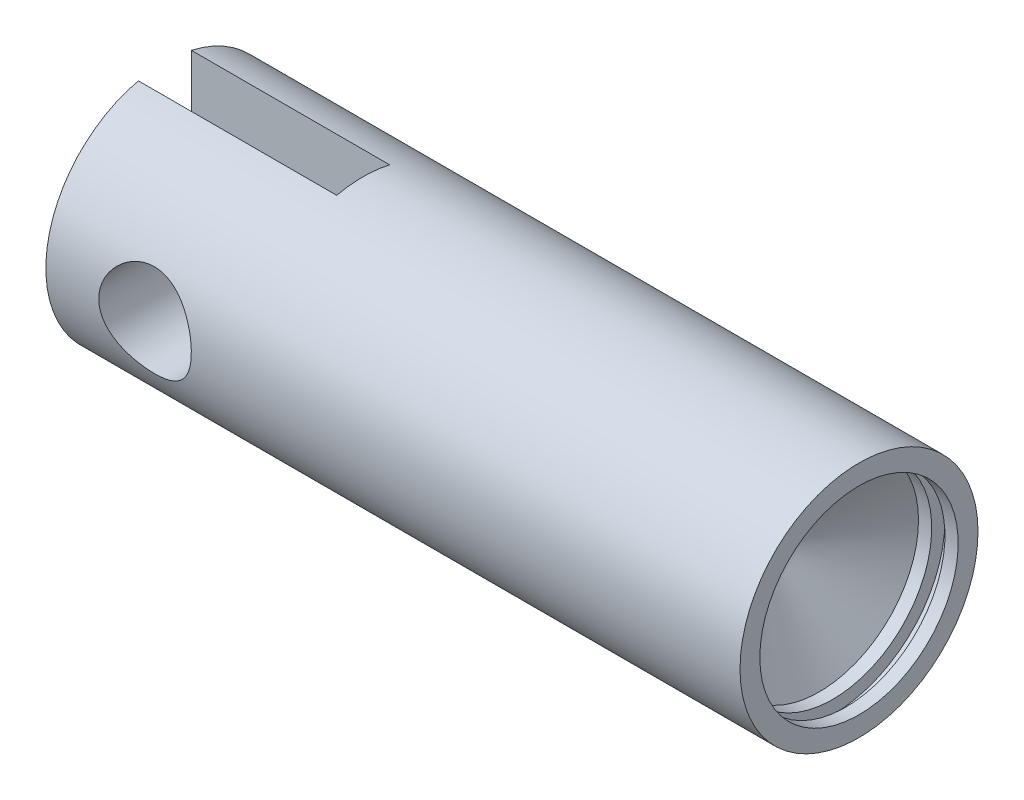
SolidWorks part; units mm, degrees
material "Acier allié inoxydable"
ref_plane "Plan de face" through (0, 0, 0) normal (0, 0, 1) x (1, 0, 0)
ref_plane "Plan de dessus" through (0, 0, 0) normal (0, 1, 0) x (1, 0, 0)
ref_plane "Plan de droite" through (0, 0, 0) normal (1, 0, 0) x (0, 0, -1)
sketch "Esquisse1" plane through (0, 0, 0) normal (0, 0, 1) x (1, 0, 0)
  line L0 (0, 18) -> (0, 0)
  line L1 (0, 0) -> (105, 0)
  line L2 (105, 0) -> (105, 18)
  line L3 (105, 18) -> (0, 18)
  line L4 (0, 0) -> (105, 0) construction
revolve "Révolution1" add sketch "Esquisse1" angle 360 about L4
sketch "Esquisse2" plane through (0, 0, 0) normal (-1, 0, 0) x (0, 0, 1)
  line L0 (-4, 17.5499) -> (-4, -17.5499)
  arc A0 (-4, -17.5499) -> (-4, 17.5499) centre (0, 0) ccw
extrude "Enlèv. mat.-Extru.1" cut sketch "Esquisse2" against normal blind 30
sketch "Esquisse3" plane through (30, 0, 0) normal (-1, 0, 0) x (0, 0, 1)
  line L0 (4, -17.5499) -> (4, 17.5499)
  arc A0 (4, 17.5499) -> (4, -17.5499) centre (0, 0) cw
extrude "Extrusion1" add sketch "Esquisse3" along normal blind 30
ref_plane "Plan4" through (0, 0, 0) normal (0, 0, -1) x (-1, 0, 0)
sketch "Esquisse4" plane through (0, 0, 0) normal (0, 0, -1) x (-1, 0, 0)
  line L0 (-105, 15) -> (-105, 0)
  line L1 (-105, 0) -> (-90.3397, 0)
  line L2 (-90.3397, 0) -> (-99, 15)
  line L3 (-99, 15) -> (-101, 15)
  line L4 (-101, 15) -> (-101, 17)
  line L5 (-101, 17) -> (-103, 17)
  line L6 (-103, 17) -> (-103, 15)
  line L7 (-103, 15) -> (-105, 15)
  line L8 (-105, 0) -> (-90.3396, 0) construction
revolve "Enlèvement de matière-Révolution1" cut sketch "Esquisse4" angle 360 about L8
hole_wizard "Diamètre du perçage M14.0 (14)1" positions "Esquisse6" profile "Esquisse5" hole size "M14.0" standard "Ansi Métrique"
sketch "Esquisse6" plane through (0, 0, 4) normal (0, 0, -1) x (-1, 0, 0)
  point P0 (-15, 0)
sketch "Esquisse5" plane through (15, 0, 4) normal (1, 0, 0) x (0, 1, 0)
  line L0 (0, 0) -> (0, 14)
  line L1 (0, 14) -> (7, 14)
  line L2 (7, 14) -> (7, 0)
  line L5 (7, 0) -> (0, 0)
  line L11 (0, -6.35) -> (0, 107.95) construction
  dimension "Diamètre du perçage jusqu'au prochain" = 14
  dimension "Profondeur du perçage jusqu'au prochain" = 14
hole_wizard "Diamètre du perçage M14.0 (14)2" positions "Esquisse8" profile "Esquisse7" hole size "M14.0" standard "Ansi Métrique"
sketch "Esquisse8" plane through (0, 0, -4) normal (0, 0, 1) x (1, 0, 0)
  point P0 (15, 0)
sketch "Esquisse7" plane through (15, 0, -4) normal (1, 0, 0) x (0, -1, 0)
  line L0 (0, 0) -> (0, 14)
  line L1 (0, 14) -> (7, 14)
  line L2 (7, 14) -> (7, 0)
  line L5 (7, 0) -> (0, 0)
  line L11 (0, -6.35) -> (0, 107.95) construction
  dimension "Diamètre du perçage jusqu'au prochain" = 14
  dimension "Profondeur du perçage jusqu'au prochain" = 14
